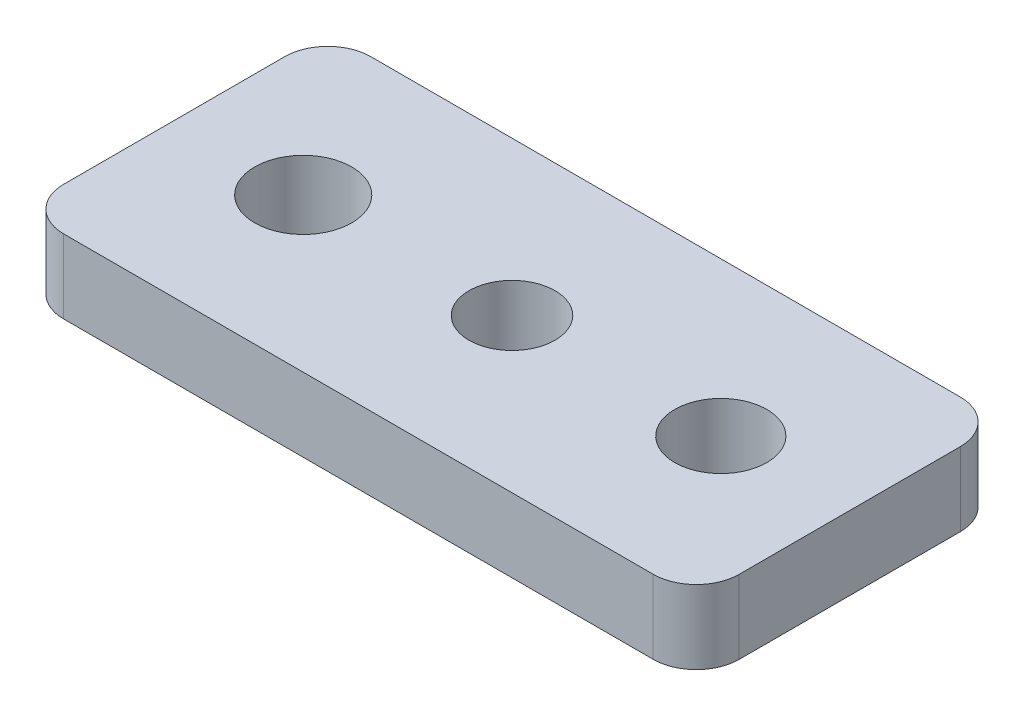
SolidWorks part; units mm, degrees
ref_plane "Front Plane" through (0, 0, 0) normal (0, 0, 1) x (1, 0, 0)
ref_plane "Top Plane" through (0, 0, 0) normal (0, 1, 0) x (1, 0, 0)
ref_plane "Right Plane" through (0, 0, 0) normal (1, 0, 0) x (0, 0, -1)
sketch "Sketch1" plane through (0, 0, 0) normal (0, 1, 0) x (1, 0, 0)
  line L1 (-27.5, 12.5) -> (27.5, 12.5)
  line L2 (-27.5, 12.5) -> (-27.5, -12.5)
  line L3 (-27.5, -12.5) -> (27.5, -12.5)
  line L4 (27.5, 12.5) -> (27.5, -12.5)
  line L5 (-27.5, 12.5) -> (27.5, -12.5) construction
  line L6 (-27.5, -12.5) -> (27.5, 12.5) construction
  point P0 (0, 0)
  dimension "D1" = 25
  dimension "D2" = 55
extrude "Boss-Extrude1" add sketch "Sketch1" along normal blind 6
sketch "Sketch2" plane through (0, 6, 0) normal (0, 1, 0) x (1, 0, 0)
  circle A0 centre (0, 0) radius 3.5
  circle A1 centre (17, 0) radius 3.75
  circle A2 centre (-17, 0) radius 3.95
  dimension "D1" = 17
  dimension "D2" = 17
extrude "Cut-Extrude1" cut sketch "Sketch2" against normal blind 6
fillet "Fillet1" radius 3.5 4 edges at (27.5, 3, -12.5) (-27.5, 3, -12.5) (-27.5, 3, 12.5) (27.5, 3, 12.5)
